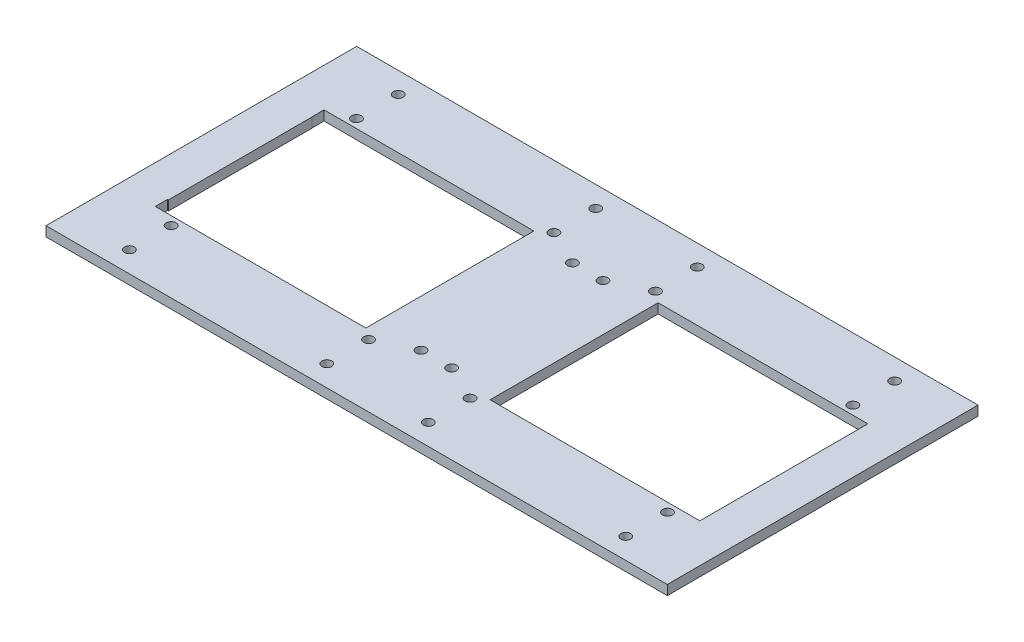
SolidWorks part; units mm, degrees
ref_plane "Front" through (0, 0, 0) normal (0, 0, 1) x (1, 0, 0)
ref_plane "Top" through (0, 0, 0) normal (0, 1, 0) x (1, 0, 0)
ref_plane "Right" through (0, 0, 0) normal (1, 0, 0) x (0, 0, -1)
sketch "Sketch1" plane through (0, 0, 0) normal (0, 1, 0) x (1, 0, 0)
  line L0 (0, -50.8) -> (203.2, -50.8)
  line L1 (0, 0) -> (203.2, 0)
  line L2 (0, 0) -> (0, -101.6)
  line L3 (0, -101.6) -> (203.2, -101.6)
  line L4 (203.2, 0) -> (203.2, -101.6)
  line L5 (101.6, 0) -> (0, 0)
  line L6 (50.8, 0) -> (50.8, -101.6)
  line L7 (101.6, 0) -> (203.2, 0)
  line L8 (152.4, 0) -> (152.4, -101.6)
  line L9 (12.7, -27.3231) -> (12.7, -74.2769)
  line L10 (81.28, -27.3231) -> (81.28, -74.2769)
  line L11 (12.7, -27.3231) -> (81.28, -27.3231)
  line L12 (12.7, -74.2769) -> (81.28, -74.2769)
  line L14 (121.92, -27.3231) -> (121.92, -74.2769)
  line L15 (101.6, 0) -> (101.6, -101.6)
  line L16 (12.7, 0) -> (12.7, -13.6616)
  line L17 (12.7, -13.6616) -> (12.7, -27.3231)
  line L18 (12.7, -74.2769) -> (12.7, -87.9384)
  line L19 (12.7, -87.9384) -> (12.7, -101.6)
  line L20 (190.5, -27.3231) -> (121.92, -27.3231)
  line L22 (190.5, -74.2769) -> (121.92, -74.2769)
  line L23 (190.5, -27.3231) -> (121.92, -27.3231)
  line L24 (106.6, -26.05) -> (96.6, -26.05)
  line L25 (106.6, -26.05) -> (106.6, -75.55)
  line L26 (106.6, -75.55) -> (96.6, -75.55)
  line L27 (96.6, -26.05) -> (96.6, -75.55)
  line L28 (106.6, -26.05) -> (96.6, -75.55) construction
  line L29 (106.6, -75.55) -> (96.6, -26.05) construction
  line L31 (121.92, -27.3231) -> (121.92, -23.3231)
  line L32 (190.5, -23.3231) -> (121.92, -23.3231)
  line L33 (190.5, -74.2769) -> (121.92, -74.2769)
  line L34 (190.5, -74.2769) -> (190.5, -78.2769)
  line L35 (121.92, -74.2769) -> (121.92, -78.2769)
  line L36 (190.5, -78.2769) -> (121.92, -78.2769)
  line L37 (81.28, -74.2769) -> (81.28, -78.2769)
  line L38 (81.28, -74.2769) -> (12.4051, -74.2769)
  line L39 (81.28, -78.2769) -> (12.4051, -78.2769)
  line L40 (12.4051, -74.2769) -> (12.4051, -78.2769)
  line L41 (81.28, -27.3231) -> (81.28, -23.3231)
  line L42 (81.28, -27.3231) -> (12.6484, -27.3231)
  line L43 (81.28, -23.3231) -> (12.6484, -23.3231)
  line L44 (12.6484, -27.3231) -> (12.6484, -23.3231)
  line L45 (118.2, -6.8308) -> (118.2, -20.4924)
  line L46 (190.5, -23.3231) -> (190.5, -27.3231)
  line L47 (190.5, -74.2769) -> (190.5, -27.3231)
  circle A0 centre (12.7, -6.8308) radius 1.6
  circle A1 centre (12.7, -81.1076) radius 1.6
  circle A2 centre (12.7, -94.7692) radius 1.6
  circle A3 centre (12.7, -20.4924) radius 1.6
  circle A4 centre (190.5, -94.7692) radius 1.6
  circle A5 centre (190.5, -81.1076) radius 1.6
  circle A6 centre (190.5, -6.8308) radius 1.6
  circle A7 centre (190.5, -20.4924) radius 1.6
  circle A8 centre (118.2, -6.8308) radius 1.6
  circle A10 centre (118.2, -94.7692) radius 1.6
  circle A12 centre (85, -94.7692) radius 1.6
  circle A15 centre (85, -6.8308) radius 1.6
  circle A16 centre (106.6, -26.05) radius 1.6
  circle A17 centre (96.6, -26.05) radius 1.6
  circle A18 centre (106.6, -75.55) radius 1.6
  circle A19 centre (96.6, -75.55) radius 1.6
  circle A20 centre (118.2, -20.4924) radius 1.6
  circle A21 centre (118.2, -81.1076) radius 1.6
  circle A22 centre (85, -81.1076) radius 1.6
  circle A23 centre (85, -20.4924) radius 1.6
  circle A24 centre (182.769, -6.8308) radius 1.6
  circle A25 centre (182.769, -20.4924) radius 1.6
  circle A26 centre (182.769, -94.7692) radius 1.6
  circle A27 centre (182.769, -81.1076) radius 1.6
  circle A28 centre (20.431, -94.7692) radius 1.6
  circle A29 centre (20.431, -81.1076) radius 1.6
  circle A30 centre (20.431, -20.4924) radius 1.6
  circle A31 centre (20.431, -6.8308) radius 1.6
  point P15 (12.7, -50.8)
  point P16 (12.7, -50.8)
  point P19 (81.28, -50.8)
  point P60 (101.6, -50.8)
  dimension "D5" = 10
  dimension "D7" = 46.9537
  dimension "D1" = 101.6
  dimension "D2" = 203.2
  dimension "D3" = 30.48
  dimension "D4" = 38.1
  dimension "D6" = 49.5
  dimension "D8" = 4
  dimension "D9" = 4
  dimension "D10" = 85
extrude "Boss-Extrude1" add sketch "Sketch1" against normal blind 3.175
